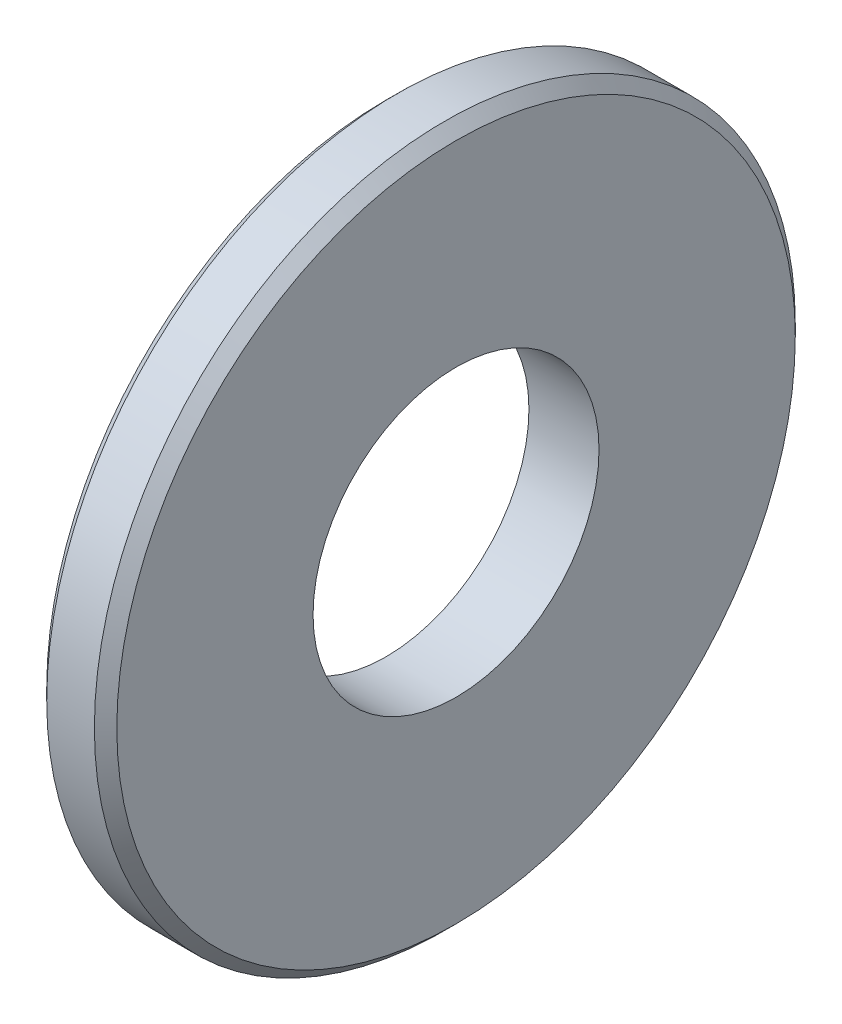
SolidWorks part; units mm, degrees
material "Brass"
ref_plane "Front Plane" through (0, 0, 0) normal (0, 0, 1) x (1, 0, 0)
ref_plane "Top Plane" through (0, 0, 0) normal (0, 1, 0) x (1, 0, 0)
ref_plane "Right Plane" through (0, 0, 0) normal (1, 0, 0) x (0, 0, -1)
sketch "Sketch1" plane through (0, 0, 0) normal (1, 0, 0) x (0, 0, -1)
  circle A0 centre (0, 0) radius 3.2385
  circle A1 centre (0, 0) radius 7.9375
  dimension "D1" = 6.477
  dimension "D2" = 15.875
extrude "Boss-Extrude1" add sketch "Sketch1" along normal blind 1.5875
chamfer "Chamfer1" distance 0.254 angle 45 2 edges at (0, 0, -7.9375) (1.5875, 0, -7.9375)
